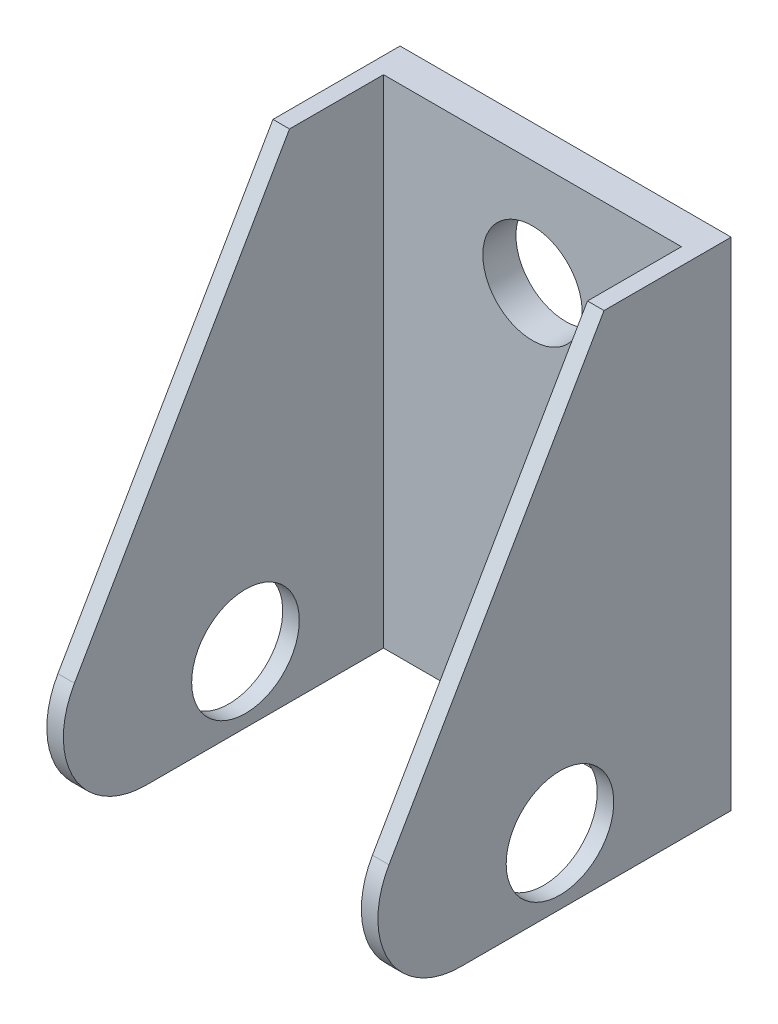
SolidWorks part; units mm, degrees
ref_plane "Front Plane" through (0, 0, 0) normal (0, 0, 1) x (1, 0, 0)
ref_plane "Top Plane" through (0, 0, 0) normal (0, 1, 0) x (1, 0, 0)
ref_plane "Right Plane" through (0, 0, 0) normal (1, 0, 0) x (0, 0, -1)
sketch "Sketch1" plane through (0, 0, 0) normal (0, 0, 1) x (1, 0, 0)
  line L5 (-10, -15) -> (10, -15)
  line L6 (-10, -15) -> (-10, 15)
  line L7 (-10, 15) -> (10, 15)
  line L8 (10, -15) -> (10, 15)
  line L9 (-10, -15) -> (10, 15) construction
  line L10 (-10, 15) -> (10, -15) construction
  point P0 (0, 0)
  dimension "D1" = 30
  dimension "D2" = 20
extrude "Boss-Extrude1" add sketch "Sketch1" along normal blind 2
sketch "Sketch2" plane through (10, 0, 0) normal (1, 0, 0) x (0, 0, -1)
  line L0 (-2, 15) -> (-7.6795, 15)
  line L1 (-2, -15) -> (-25, -15)
  line L2 (-25, -15) -> (-7.6795, 15)
  line L7 (0, -15) -> (0, 15)
  line L8 (0, 15) -> (-2, 15)
  line L9 (-2, 15) -> (-2, -15)
  line L10 (-2, -15) -> (0, -15)
  line L13 (-2, 15) -> (-2, -15)
  dimension "D1" = 60
  dimension "D3" = 0
extrude "Boss-Extrude2" add sketch "Sketch2" against normal blind 1
pattern_linear "LPattern1" count 2 spacing 19 along (-1, 0, 0) of "Boss-Extrude2"
fillet "Fillet1" radius 5 1 edges at (-9.5, -15, 25)
fillet "Fillet2" radius 5 1 edges at (9.5, -15, 25)
sketch "Sketch3" plane through (-10, 0, 0) normal (-1, 0, 0) x (0, 0, 1)
  line L0 (16.3397, -15) -> (0, -15) construction
  line L2 (0, 15) -> (0, -15) construction
  arc A0 (16.3397, -15) -> (20.6699, -7.5) centre (16.3397, -10) ccw construction
  circle A1 centre (10.3397, -11) radius 3.25
  point P0 (10.3397, -11)
  dimension "D4" = 6.5
  dimension "D1" = 4
  dimension "D2" = 6
  dimension "D3" = 10.3397
extrude "Cut-Extrude1" cut sketch "Sketch3" against normal through all
sketch "Sketch4" plane through (0, 0, 0) normal (0, 0, -1) x (-1, 0, 0)
  circle A0 centre (0, 8.5889) radius 3
  dimension "D1" = 6
extrude "Cut-Extrude2" cut sketch "Sketch4" against normal through all
